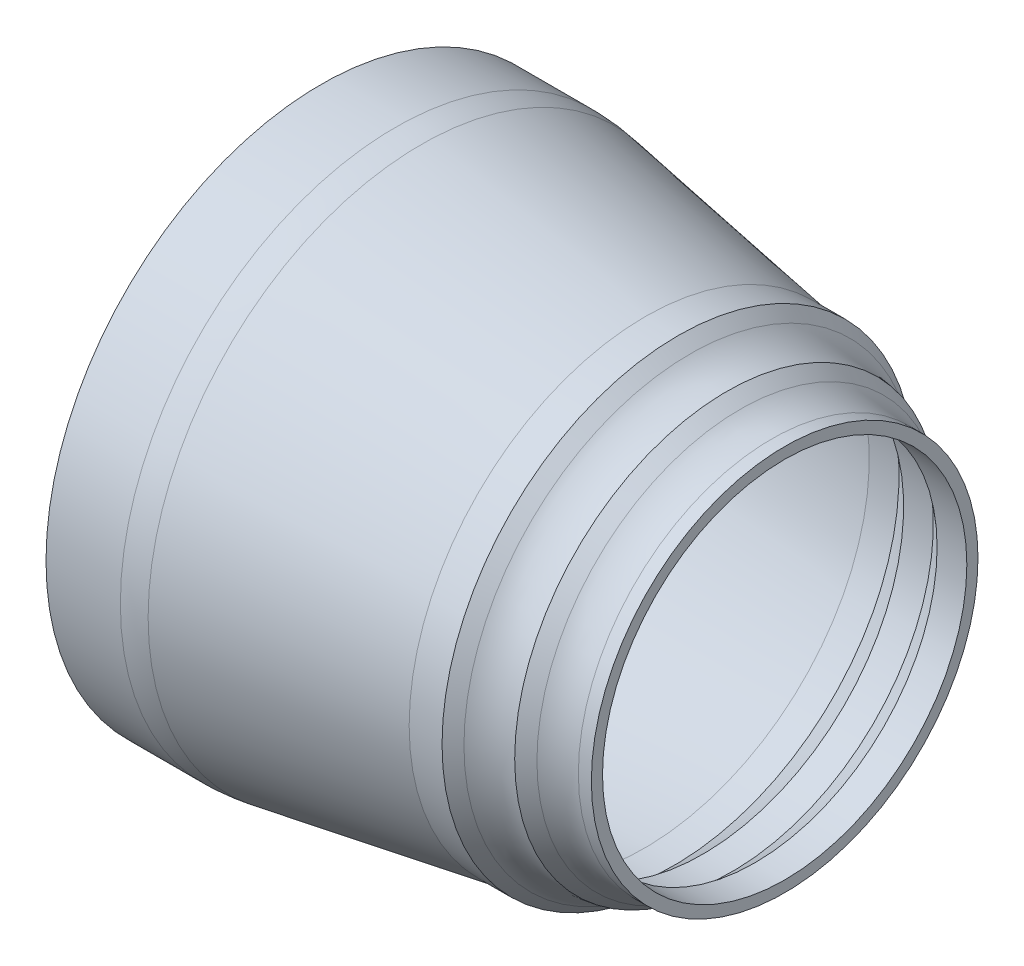
SolidWorks part; units mm, degrees
ref_plane "Front Plane" through (0, 0, 0) normal (0, 0, 1) x (1, 0, 0)
ref_plane "Top Plane" through (0, 0, 0) normal (0, 1, 0) x (1, 0, 0)
ref_plane "Right Plane" through (0, 0, 0) normal (1, 0, 0) x (0, 0, -1)
sketch "Sketch3" plane through (0, 0, 0) normal (0, 0, 1) x (1, 0, 0)
  line L0 (-206, -98) -> (-190, -98)
  line L1 (-190, -98) -> (-190, -104)
  line L2 (-206, -98) -> (-218, -108)
  line L3 (-218, -108) -> (-234, -108)
  line L4 (-234, -108) -> (-249.5, -121)
  line L5 (-249.5, -121) -> (-265.5, -121)
  line L6 (-190, -104) -> (-197, -104)
  line L7 (-214, -109.2816) -> (-221.0859, -114.1549)
  line L8 (-265.5, -121) -> (-386.5, -140.988)
  line L9 (-399.3264, -141.9884) -> (-432.8264, -141.9884)
  line L10 (-439.3746, -147.9882) -> (-399.3746, -147.9882)
  line L11 (-439.3746, -147.9882) -> (-438.5094, -145.3253)
  line L12 (-230.1443, -112.5971) -> (-247.317, -127) construction
  line L13 (-240.9122, -121.6283) -> (-247.317, -127)
  line L14 (-247.317, -127) -> (-265.0078, -127)
  line L15 (-265.0078, -127) -> (-385.5221, -146.9078)
  line L16 (0, 0) -> (207.9115, 0) construction
  arc A0 (-221.0859, -114.1549) -> (-240.9122, -121.6283) centre (-220.3486, -146.1464) ccw
  arc A1 (-197, -104) -> (-214, -109.2816) centre (-197, -134) ccw
  arc A2 (-386.5, -140.988) -> (-399.3264, -141.9884) centre (-398.7236, -66.9908) cw
  arc A3 (-385.5221, -146.9078) -> (-399.3746, -147.9882) centre (-398.7236, -66.9908) cw
  spline S0 degree 3 poles (-438.5094, -145.3253) (-438.0929, -144.0436) (-435.7437, -142.3893) (-433.5836, -141.9884) (-432.8264, -141.9884) knots 0 0 0 0 0.670787 1 1 1 1
  dimension "D12" = 30
  dimension "D15" = 170.62
  dimension "D16" = 32
  dimension "D18" = 75
  dimension "D24" = 2.8
  dimension "D23" = 2.2
  dimension "D1" = 98
  dimension "D2" = 190
  dimension "D3" = 16
  dimension "D4" = 6
  dimension "D5" = 12
  dimension "D6" = 10
  dimension "D7" = 16
  dimension "D8" = 15.5
  dimension "D9" = 13
  dimension "D10" = 16
  dimension "D11" = 7
  dimension "D13" = 17
  dimension "D14" = 8.6
  dimension "D17" = 121
  dimension "D19" = 33.5
  dimension "D20" = 40
  dimension "D21" = 5.6
  dimension "D22" = 72
  dimension "D25" = 6
revolve "Revolve3" add sketch "Sketch3" angle 360 about L16
